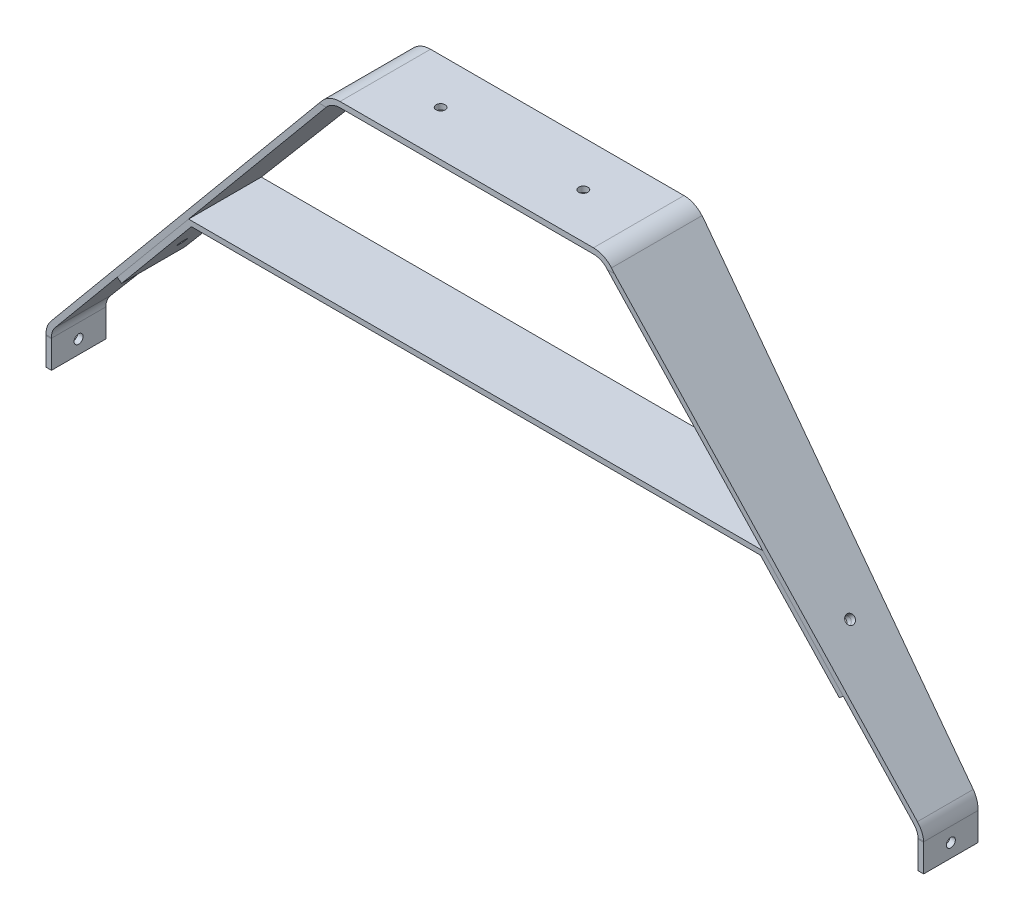
SolidWorks part; units mm, degrees
material "Thornel Mat VMA"
ref_plane "Front Plane" through (0, 0, 0) normal (0, 0, 1) x (1, 0, 0)
ref_plane "Top Plane" through (0, 0, 0) normal (0, 1, 0) x (1, 0, 0)
ref_plane "Right Plane" through (0, 0, 0) normal (1, 0, 0) x (0, 0, -1)
sketch "Sketch2" plane through (0, 0, 0) normal (0, 0, 1) x (1, 0, 0)
  line L0 (0, 0) -> (0, 15.3603)
  line L1 (2.3396, 21.7882) -> (161.7685, 211.7882)
  line L2 (169.4289, 215.3603) -> (239.4289, 215.3603)
  line L3 (-3, 0) -> (-3, 15.3603)
  line L4 (0.0414, 23.7165) -> (159.4704, 213.7165)
  line L5 (169.4289, 218.3603) -> (239.4289, 218.3603)
  line L6 (239.4289, 218.3603) -> (239.4289, 215.3603)
  line L7 (-3, 0) -> (0, 0)
  arc A0 (169.4289, 215.3603) -> (161.7685, 211.7882) centre (169.4289, 205.3603) ccw
  arc A1 (2.3396, 21.7882) -> (0, 15.3603) centre (10, 15.3603) ccw
  arc A2 (0.0414, 23.7165) -> (-3, 15.3603) centre (10, 15.3603) ccw
  arc A3 (169.4289, 218.3603) -> (159.4704, 213.7165) centre (169.4289, 205.3603) ccw
  dimension "D1" = 10
  dimension "D2" = 10
  dimension "D4" = 70
  dimension "D5" = 200
  dimension "D3" = 3
extrude "Boss-Extrude1" add sketch "Sketch2" along normal mid plane 50
ref_plane "Plane1" through (161.7685, 0, 0) normal (1, 0, 0) x (0, 0, -1)
sketch "Sketch3" plane through (161.7685, 0, 0) normal (1, 0, 0) x (0, 0, -1)
  line L0 (25, 211.7882) -> (25, 15.3603)
  line L2 (-25, 15.3603) -> (25, 15.3603) construction
  line L3 (15.0129, 15.6144) -> (25, 211.7882)
  line L4 (-25, 211.7882) -> (-25, 15.3603)
  line L6 (-15.0129, 15.6144) -> (-25, 211.7882)
  line L7 (-15, 15.1059) -> (-15, 0)
  line L8 (-25, 0) -> (25, 0) construction
  line L9 (-15, 0) -> (-25, 0)
  line L10 (-25, 0) -> (-25, 15.3603)
  line L11 (15, 15.1059) -> (15, 0)
  line L12 (15, 0) -> (25, 0)
  line L13 (25, 0) -> (25, 15.3603)
  arc A0 (15.0129, 15.6144) -> (15, 15.1059) centre (25, 15.1059) ccw
  arc A1 (-15.0129, 15.6144) -> (-15, 15.1059) centre (-25, 15.1059) cw
  point P22 (15, 15.3603)
  point P25 (-15, 15.3603)
  dimension "D1" = 10
  dimension "D2" = 10
  dimension "D3" = 10
extrude "Cut-Extrude1" cut sketch "Sketch3" against normal through all both and the other way through all contours L6 L4 L10 L9 L7 A1 | L0 L13 L12 L11 A0 L3
sketch "Sketch5" [suppressed] plane through (161.7685, 0, 0) normal (1, 0, 0) x (0, 0, -1)
  line L0 (25, 211.7882) -> (25, 0)
  line L1 (25, 0) -> (15, 0)
  line L2 (-15, 0) -> (15, 0) construction
  line L3 (15, 0) -> (15, 15.1059)
  line L4 (-15.0032, 15.3603) -> (15.0032, 15.3603) construction
  line L5 (25, 211.7882) -> (15.0129, 15.6144)
  arc A0 (15, 15.1059) -> (15.0129, 15.6144) centre (25, 15.1059) cw
  point P13 (15, 15.3603)
  dimension "D1" = 10
  dimension "D2" = 10
extrude "Cut-Extrude2" [suppressed] cut sketch "Sketch5" against normal through all both and the other way through all contours L3 A0 L5 L0 L1
sketch "Sketch6" plane through (0, 0, 0) normal (0, 1, 0) x (1, 0, 0)
  circle A0 centre (200, 0) radius 2.5
  dimension "D1" = 200
  dimension "D2" = 5
extrude "Cut-Extrude3" cut sketch "Sketch6" along normal through all both and the other way through all contours A0
sketch "Sketch7" plane through (161.7685, 0, 0) normal (1, 0, 0) x (0, 0, -1)
  circle A0 centre (0, 7.5) radius 2.5
  dimension "D1" = 7.5
  dimension "D2" = 5
extrude "Cut-Extrude4" cut sketch "Sketch7" against normal through all both and the other way through all
mirror "Mirror2" about plane through (239.4289, 218.3603, 25) normal (-1, 0, 0) of "Cut-Extrude4", "Cut-Extrude3", "Cut-Extrude1", "Boss-Extrude1", "Cut-Extrude2"
sketch "Sketch9" plane through (0, 0, 25) normal (0, 0, 1) x (1, 0, 0)
  line L0 (80.8559, 115.3603) -> (398.002, 115.3603)
  line L1 (161.7685, 211.7882) -> (2.3396, 21.7882) construction
  line L2 (476.5183, 21.7882) -> (317.0894, 211.7882) construction
  line L3 (398.002, 115.3603) -> (439.957, 65.3603)
  line L4 (80.8559, 115.3603) -> (38.9009, 65.3603)
  line L5 (169.4289, 215.3603) -> (309.4289, 215.3603) construction
  line L6 (82.2548, 112.3603) -> (41.199, 63.4319)
  line L7 (82.2548, 112.3603) -> (396.603, 112.3603)
  line L8 (396.603, 112.3603) -> (437.6588, 63.4319)
  line L9 (38.9009, 65.3603) -> (41.199, 63.4319)
  line L10 (439.957, 65.3603) -> (437.6588, 63.4319)
  dimension "D1" = 100
  dimension "D2" = 50
  dimension "D3" = 3
extrude "Boss-Extrude2" add sketch "Sketch9" against normal up to surface (50 mm away) separate body up to face at (239.4289, 214.5933, -25)
sketch "Sketch10" plane through (0, 0, 0) normal (1, 0, 0) x (0, 0, -1)
  line L0 (25, 115.3603) -> (20.0909, 115.3603)
  line L1 (25, 115.3603) -> (-25, 115.3603) construction
  line L2 (25, 115.3603) -> (25, 63.4319)
  line L3 (25, 63.4319) -> (17.4473, 63.4319)
  line L4 (25, 63.4319) -> (-25, 63.4319) construction
  line L5 (-17.4473, 63.4319) -> (-25, 63.4319)
  line L6 (-25, 213.7165) -> (-25, 211.7882)
  line L7 (-25, 211.7882) -> (-15.4254, 23.7165)
  line L8 (-15.4254, 23.7165) -> (15.4254, 23.7165)
  line L9 (15.4254, 23.7165) -> (25, 211.7882)
  line L10 (25, 211.7882) -> (25, 213.7165)
  line L11 (25, 213.7165) -> (-25, 213.7165)
  line L13 (-20.0909, 115.3603) -> (-17.4473, 63.4319)
  line L15 (17.4473, 63.4319) -> (20.0909, 115.3603)
  line L18 (-25, 63.4319) -> (-25, 115.3603)
  line L19 (-25, 115.3603) -> (-20.0909, 115.3603)
  dimension "D1" = 0
extrude "Cut-Extrude5" cut sketch "Sketch10" against normal through all both and the other way through all
sketch "Sketch11" plane through (-7.0575, 5.922, 0) normal (0.766, -0.6428, 0) x (0, 0, -1)
  line L0 (17.4473, 75.0739) -> (-17.4473, 75.0739) construction
  circle A0 centre (0, 100.0739) radius 2.5
  dimension "D1" = 5
  dimension "D2" = 25
extrude "Cut-Extrude6" cut sketch "Sketch11" against normal through all both and the other way through all
ref_plane "Plane2" through (239.4289, 0, 0) normal (1, 0, 0) x (0, 0, -1)
mirror "Mirror3" about plane through (239.4289, 0, 0) normal (1, 0, 0) of "Cut-Extrude6"
equation "\"x\"= 176"
